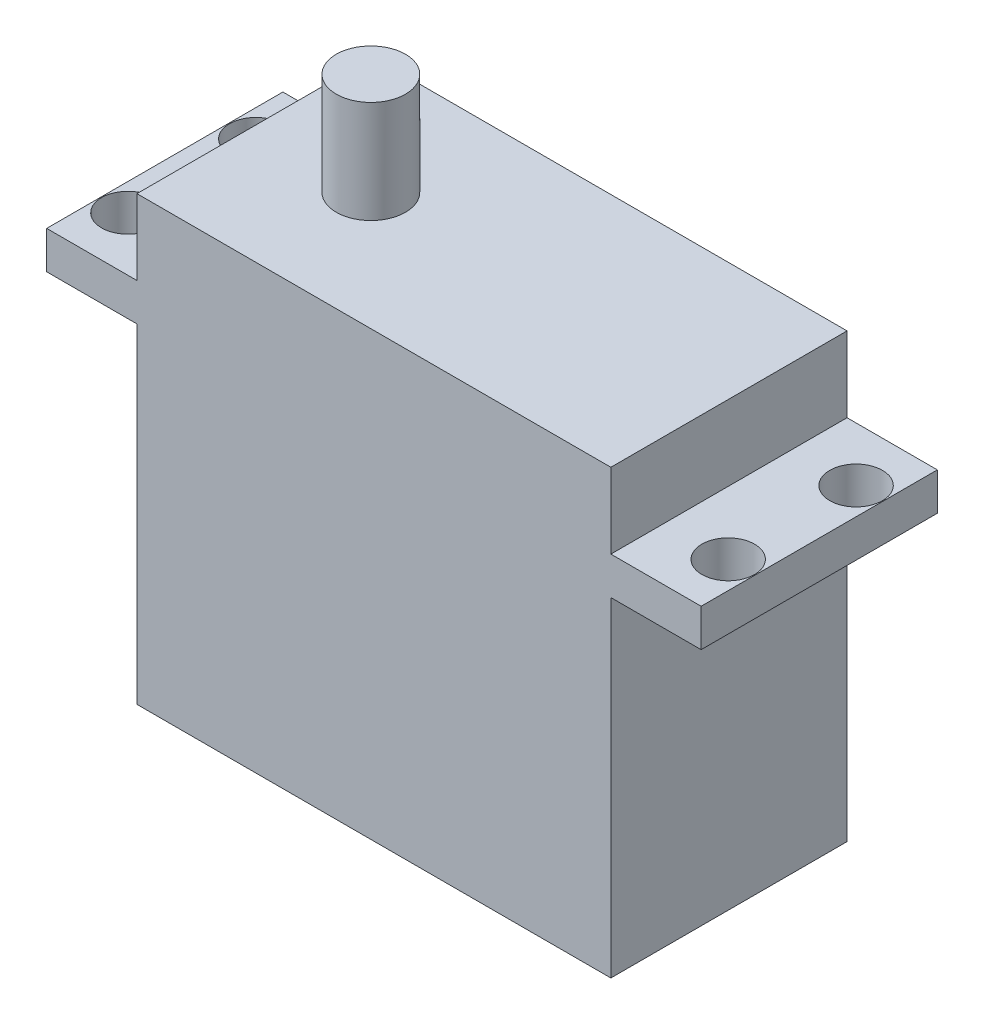
SolidWorks part; units mm, degrees
ref_plane "Front Plane" through (0, 0, 0) normal (0, 0, 1) x (1, 0, 0)
ref_plane "Top Plane" through (0, 0, 0) normal (0, 1, 0) x (1, 0, 0)
ref_plane "Right Plane" through (0, 0, 0) normal (1, 0, 0) x (0, 0, -1)
sketch "Sketch1" plane through (0, 0, 0) normal (0, 1, 0) x (1, 0, 0)
  line L1 (0, 0) -> (40.005, 0)
  line L2 (0, 0) -> (0, 19.939)
  line L3 (0, 19.939) -> (40.005, 19.939)
  line L4 (40.005, 0) -> (40.005, 19.939)
  dimension "D1" = 40.005
  dimension "D2" = 19.939
extrude "Boss-Extrude1" add sketch "Sketch1" along normal blind 37.338
sketch "Sketch2" plane through (40.005, 0, 0) normal (1, 0, 0) x (0, 0, -1)
  line L0 (0, 37.338) -> (0, 0) construction
  line L1 (0, 30.988) -> (19.939, 30.988)
  line L2 (0, 30.988) -> (0, 27.813)
  line L3 (0, 27.813) -> (19.939, 27.813)
  line L4 (19.939, 30.988) -> (19.939, 27.813)
  line L5 (19.939, 37.338) -> (19.939, 0) construction
  line L6 (0, 37.338) -> (19.939, 37.338) construction
  dimension "D1" = 6.35
  dimension "D2" = 3.175
extrude "Boss-Extrude2" add sketch "Sketch2" along normal blind 7.62
sketch "Sketch3" plane through (0, 30.988, 0) normal (0, 1, 0) x (1, 0, 0)
  line L0 (45.339, 15.367) -> (45.339, 4.572) construction
  line L1 (47.625, 19.939) -> (47.625, 0) construction
  line L2 (47.625, 19.939) -> (40.005, 19.939) construction
  circle A0 centre (45.339, 15.367) radius 2.2225
  circle A1 centre (45.339, 4.572) radius 2.2225
  point P4 (45.339, 9.9695)
  point P5 (47.625, 9.9695)
  point P6 (45.339, 6.7945)
  point P9 (45.339, 13.1445)
  point P10 (43.815, 19.939)
  dimension "D2" = 4.445
  dimension "D1" = 6.35
  dimension "D3" = 2.286
extrude "Cut-Extrude1" cut sketch "Sketch3" against normal through all
ref_plane "Plane1" through (20.0025, 0, 0) normal (1, 0, 0) x (0, 0, -1)
mirror "Mirror1" about plane through (20.0025, 0, 0) normal (1, 0, 0) of "Cut-Extrude1", "Boss-Extrude2"
sketch "Sketch4" plane through (0, 37.338, 0) normal (0, 1, 0) x (1, 0, 0)
  line L0 (-7.62, 19.939) -> (-7.62, 0) construction
  circle A0 centre (9.779, 9.9695) radius 2.921
  point P2 (-7.62, 9.9695)
  point P3 (12.7, 9.9695)
  point P6 (0, 0)
  dimension "D2" = 5.842
  dimension "D1" = 20.32
extrude "Boss-Extrude3" add sketch "Sketch4" along normal blind 8.636
